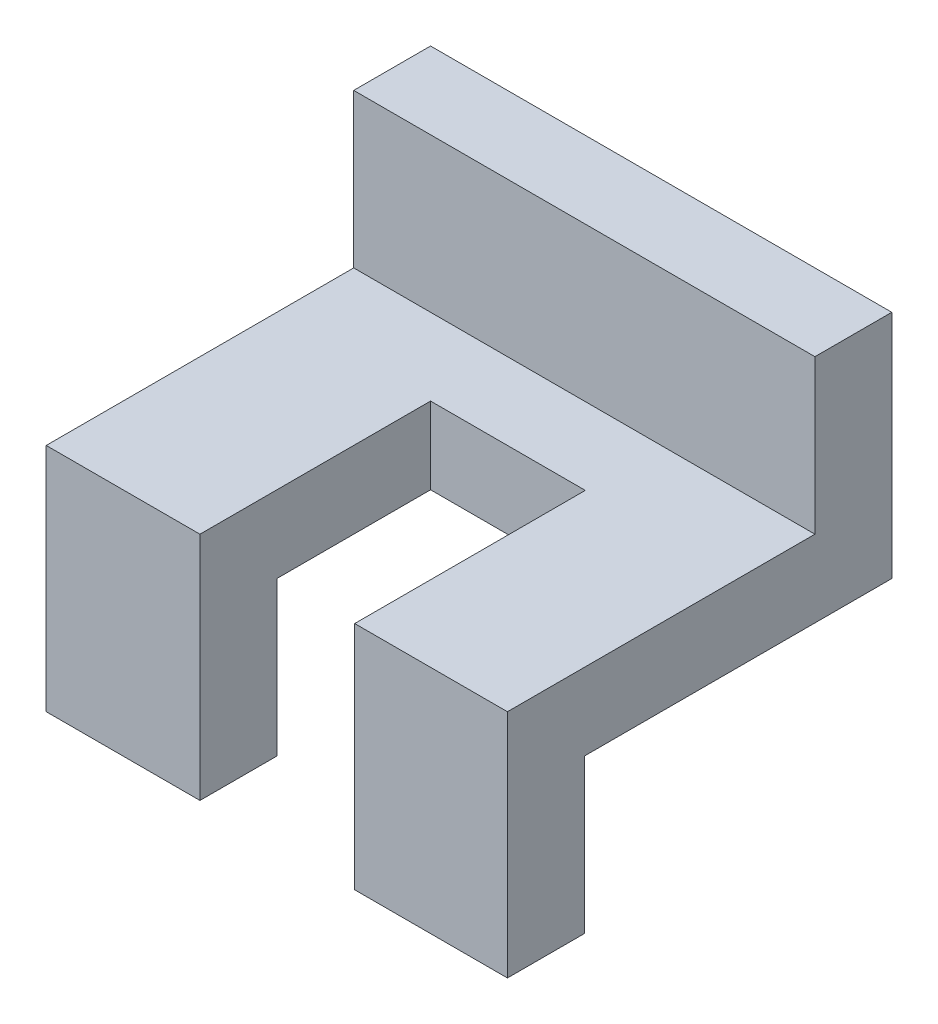
SolidWorks part; units mm, degrees
ref_plane "Front Plane" through (0, 0, 0) normal (0, 0, 1) x (1, 0, 0)
ref_plane "Top Plane" through (0, 0, 0) normal (0, 1, 0) x (1, 0, 0)
ref_plane "Right Plane" through (0, 0, 0) normal (1, 0, 0) x (0, 0, -1)
sketch "Sketch1" plane through (0, 0, 0) normal (1, 0, 0) x (0, 0, -1)
  line L0 (-9.525, -3.175) -> (-9.525, -15.875)
  line L5 (-15.875, 3.175) -> (-15.875, -15.875)
  line L6 (-9.525, -3.175) -> (15.875, -3.175)
  line L9 (-15.875, -15.875) -> (-9.525, -15.875)
  line L12 (15.875, 15.875) -> (9.525, 15.875)
  line L13 (9.525, 3.175) -> (9.525, 15.875)
  line L14 (-15.875, 3.175) -> (9.525, 3.175)
  line L15 (15.875, 15.875) -> (15.875, -3.175)
  point P0 (0, 0)
  dimension "D1" = 31.75
  dimension "D2" = 12.7
  dimension "D3" = 6.35
  dimension "D4" = 31.75
  dimension "D5" = 12.7
  dimension "D6" = 6.35
extrude "Boss-Extrude1" add sketch "Sketch1" along normal blind 38.1
sketch "Sketch2" plane through (0, 3.175, 0) normal (0, 1, 0) x (1, 0, 0)
  line L0 (38.1, -15.875) -> (0, -15.875) construction
  line L1 (12.7, -15.875) -> (25.4827, -15.875)
  line L2 (12.7, -15.875) -> (12.7, 3.175)
  line L3 (12.7, 3.175) -> (25.4827, 3.175)
  line L4 (25.4827, -15.875) -> (25.4827, 3.175)
  line L5 (0, 9.525) -> (0, -15.875) construction
  dimension "D1" = 12.7827
  dimension "D2" = 12.7
  dimension "D3" = 19.05
extrude "Cut-Extrude1" cut sketch "Sketch2" against normal through all
